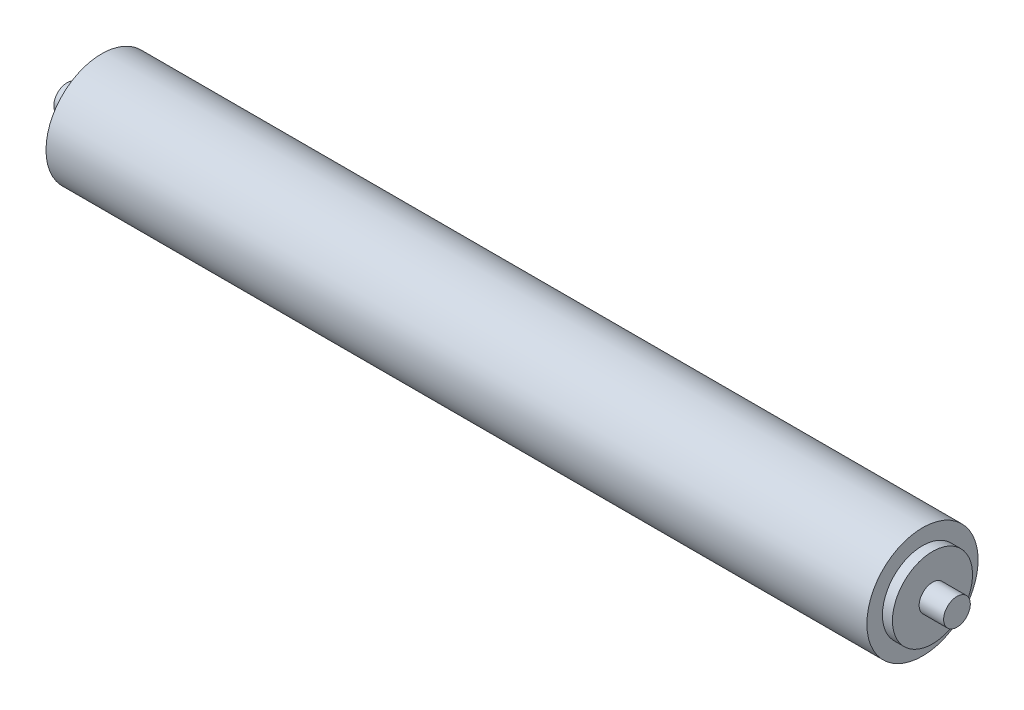
SolidWorks part; units mm, degrees
ref_plane "前视基准面" through (0, 0, 0) normal (0, 0, 1) x (1, 0, 0)
ref_plane "上视基准面" through (0, 0, 0) normal (0, 1, 0) x (1, 0, 0)
ref_plane "右视基准面" through (0, 0, 0) normal (1, 0, 0) x (0, 0, -1)
sketch "草图1" plane through (0, 0, 0) normal (0, 0, 1) x (1, 0, 0)
  line B0 (0, 0) -> (400, 0)
  line B1 (15.5, 25) -> (15.5, 18)
  line B2 (15.5, 25) -> (384.5, 25)
  line B3 (11, 6) -> (11, 18)
  line B4 (0, 6) -> (11, 6)
  line B5 (0, 6) -> (0, 0)
  line B6 (11, 18) -> (15.5, 18)
  line B7 (384.5, 25) -> (384.5, 18)
  line B8 (389, 6) -> (389, 18)
  line B9 (400, 6) -> (389, 6)
  line B10 (400, 6) -> (400, 0)
  line B11 (389, 18) -> (384.5, 18)
sketch_block_instance "A$C434904C5-1"
sketch_block "A$C434904C5"
revolve "旋转1" add sketch "草图1" angle 360 about L0
